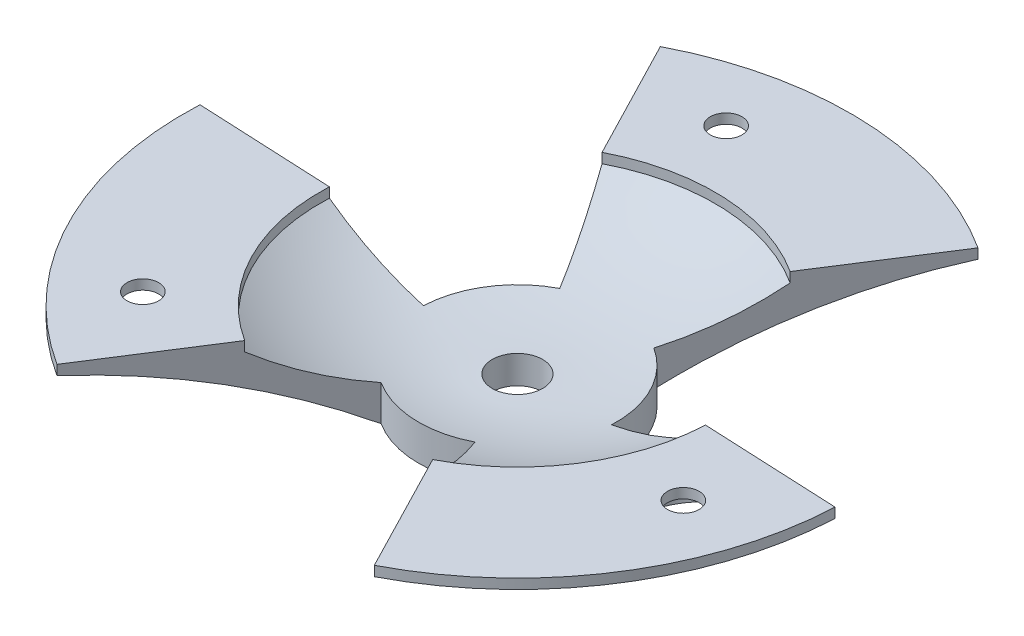
SolidWorks part; units mm, degrees
ref_plane "Front Plane" through (0, 0, 0) normal (0, 0, 1) x (1, 0, 0)
ref_plane "Top Plane" through (0, 0, 0) normal (0, 1, 0) x (1, 0, 0)
ref_plane "Right Plane" through (0, 0, 0) normal (1, 0, 0) x (0, 0, -1)
sketch "Sketch1" plane through (0, 0, 0) normal (0, 0, 1) x (1, 0, 0)
  line L1 (12.4635, 0) -> (22.4649, 0)
  line L2 (22.4649, 0) -> (22.4649, 3)
  line L3 (-11.3051, 8.8105) -> (2.4649, 8.8105)
  line L4 (-11.3051, 7.8105) -> (-11.3051, 8.8105)
  line L5 (2.4649, 7.8105) -> (2.4649, 8.8105)
  arc A0 (-11.3051, 7.8105) -> (12.4635, 0) centre (-17.6381, -51.5327) cw
  arc A1 (2.4649, 7.8105) -> (22.4649, 3) centre (19.3191, 33.9015) ccw
  dimension "D1" = 8.8105
  dimension "D2" = 10.0014
  dimension "D3" = 3
  dimension "D4" = 4.8105
  dimension "D5" = 7.8105
  dimension "D6" = 13.77
revolve "Revolve3" add sketch "Sketch1" angle 360 about L2
sketch "Sketch6" plane through (0, 0, 0) normal (0, -1, 0) x (-1, 0, 0)
  line L0 (-17.0749, -8.4247) -> (-2.7153, -30.8688)
  line L1 (-27.0604, -8.8831) -> (-39.2887, -32.556)
  line L4 (-32.4557, -0.4615) -> (-58.7539, -1.6763)
  line L5 (-27.8602, 8.4213) -> (-42.2474, 30.8479)
  line L6 (-27.8602, 8.4213) -> (-27.8658, 8.4177)
  line L7 (-59.073, -1.6693) -> (-58.7539, -1.6763)
  line L8 (-17.8692, 8.883) -> (-5.7722, 32.2653)
  line L9 (-12.4742, 0.4618) -> (14.1413, 1.7082)
  line L10 (-12.4742, 0.4618) -> (-12.4745, 0.4685)
  line L11 (-5.6066, 32.5381) -> (-5.7722, 32.2653)
  arc A0 (-17.0749, -8.4247) -> (-27.0604, -8.8831) centre (-22.4649, 0) cw
  arc A2 (-2.7153, -30.8688) -> (-39.2887, -32.556) centre (-22.4649, 0) cw
  arc A3 (-32.4557, -0.4615) -> (-27.8658, 8.4177) centre (-22.4649, 0) cw
  arc A4 (-59.073, -1.6693) -> (-42.2474, 30.8479) centre (-22.4649, 0) cw
  arc A5 (-17.8692, 8.883) -> (-12.4745, 0.4685) centre (-22.4649, 0) cw
  arc A6 (-5.6066, 32.5381) -> (14.1413, 1.7082) centre (-22.4649, 0) cw
  circle A7 centre (-2.2404, -17.7212) radius 1.6
  circle A8 centre (-47.9242, -8.6543) radius 1.6
  circle A9 centre (-17.2302, 26.3755) radius 1.6
  point P26 (-22.4649, 0)
  point P34 (-22.4649, 0)
  dimension "D1" = 26.89
  dimension "D3" = 3
extrude "Cut-Extrude3" cut sketch "Sketch6" against normal blind 25.4
hole_wizard "1/4-20 Tapped Hole2" positions "Sketch18" profile "Sketch17" tap size "1/4-20" standard "ANSI Inch" end condition through all
sketch "Sketch18" plane through (0, 0, 0) normal (0, -1, 0) x (-1, 0, 0)
  point P0 (-22.4649, 0)
sketch "Sketch17" plane through (22.4649, 0, 0) normal (1, 0, 0) x (0, 0, -1)
  line L0 (0, 0) -> (0, 10.2628)
  line L1 (0, 10.2628) -> (2.5527, 10.2628)
  line L2 (2.5527, 10.2628) -> (2.5527, 0)
  line L5 (2.5527, 0) -> (0, 0)
  line L11 (0, -6.35) -> (0, 107.95) construction
  dimension "Thru Tap Drill Dia." = 5.1054
  dimension "Thru Tap Drill Depth" = 10.2628
cosmetic thread "Hole Thread2" parameters "D2"=6.35
sketch "Sketch20" plane through (0, 0, 0) normal (0, 1, 0) x (1, 0, 0)
  circle A0 centre (2.2404, -17.7212) radius 4
  circle A1 centre (17.2302, 26.3755) radius 4
  circle A2 centre (47.9242, -8.6543) radius 4
extrude "Cut-Extrude4" cut sketch "Sketch20" along normal blind 7.81
